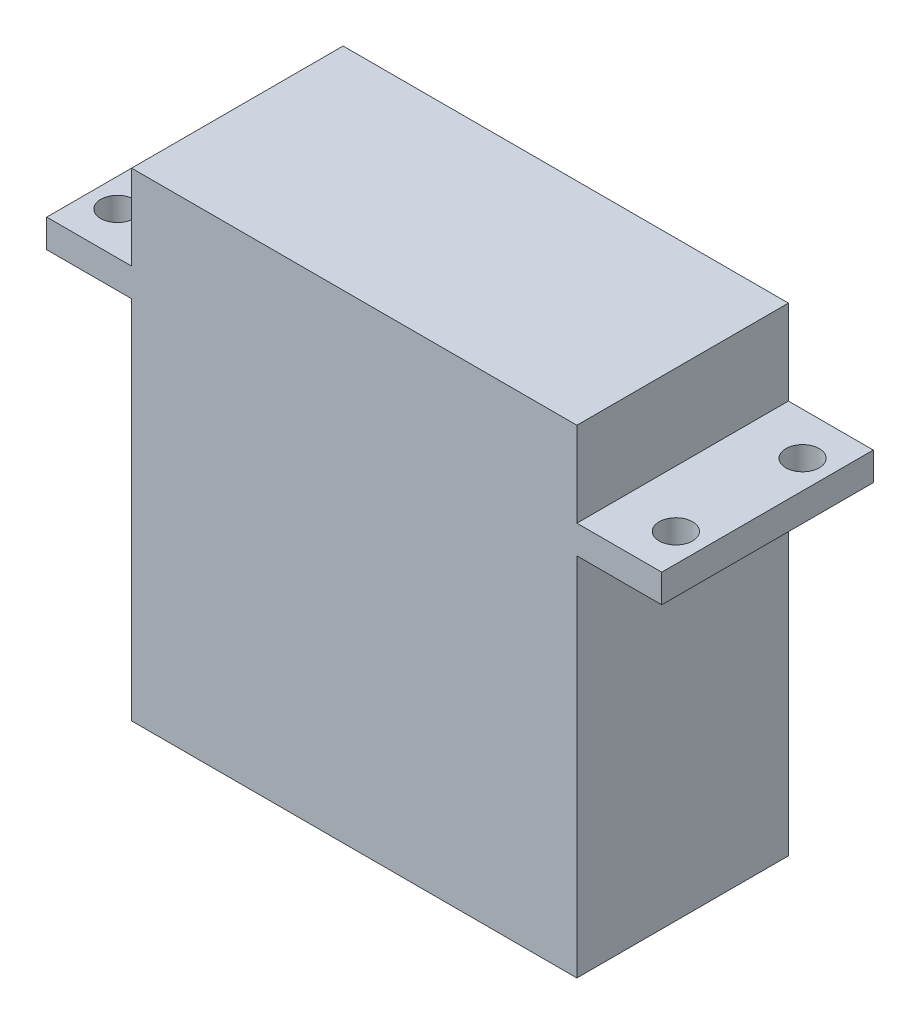
SolidWorks part; units mm, degrees
ref_plane "Front Plane" through (0, 0, 0) normal (0, 0, 1) x (1, 0, 0)
ref_plane "Top Plane" through (0, 0, 0) normal (0, 1, 0) x (1, 0, 0)
ref_plane "Right Plane" through (0, 0, 0) normal (1, 0, 0) x (0, 0, -1)
sketch "Sketch1" plane through (0, 0, 0) normal (0, 0, 1) x (1, 0, 0)
  line L1 (0, 0) -> (40, 0)
  line L2 (0, 0) -> (0, 43)
  line L3 (0, 43) -> (40, 43)
  line L4 (40, 0) -> (40, 43)
  dimension "D1" = 40
  dimension "D2" = 43
extrude "Boss-Extrude1" add sketch "Sketch1" along normal blind 19
sketch "Sketch2" plane through (40, 0, 0) normal (1, 0, 0) x (0, 0, -1)
  line L0 (-19, 0) -> (-19, 43) construction
  line L1 (-19, 35.38) -> (0, 35.38)
  line L2 (-19, 35.38) -> (-19, 32.84)
  line L3 (-19, 32.84) -> (0, 32.84)
  line L4 (0, 35.38) -> (0, 32.84)
  line L5 (0, 0) -> (0, 43) construction
  line L6 (-19, 43) -> (0, 43) construction
  dimension "D1" = 2.54
  dimension "D2" = 7.62
extrude "Boss-Extrude2" add sketch "Sketch2" along normal blind 7.62
sketch "Sketch3" plane through (0, 35.38, 0) normal (0, 1, 0) x (1, 0, 0)
  line L0 (47.62, 0) -> (40, 0) construction
  line L1 (47.62, 0) -> (47.62, -19) construction
  line L2 (47.62, -19) -> (40, -19) construction
  circle A0 centre (45.08, -3.81) radius 1.5
  circle A1 centre (45.08, -15.19) radius 1.5
  dimension "D1" = 3
  dimension "D2" = 3.81
  dimension "D3" = 2.54
  dimension "D4" = 2.54
  dimension "D5" = 3.81
extrude "Cut-Extrude1" cut sketch "Sketch3" against normal through all
sketch "Sketch4" plane through (0, 0, 0) normal (-1, 0, 0) x (0, 0, 1)
  line L0 (0, 43) -> (0, 0) construction
  line L1 (0, 35.38) -> (19, 35.38)
  line L2 (0, 35.38) -> (0, 32.84)
  line L3 (0, 32.84) -> (19, 32.84)
  line L4 (19, 35.38) -> (19, 32.84)
  line L5 (19, 43) -> (19, 0) construction
  line L6 (19, 43) -> (0, 43) construction
  dimension "D1" = 2.54
  dimension "D2" = 7.62
extrude "Boss-Extrude3" add sketch "Sketch4" along normal blind 7.62
sketch "Sketch5" plane through (0, 35.38, 0) normal (0, 1, 0) x (1, 0, 0)
  line L0 (-7.62, 0) -> (0, 0) construction
  line L1 (-7.62, -19) -> (-7.62, 0) construction
  line L2 (-7.62, -19) -> (0, -19) construction
  circle A0 centre (-5.08, -3.81) radius 1.5
  circle A1 centre (-5.08, -15.19) radius 1.5
  dimension "D1" = 3
  dimension "D4" = 3.81
  dimension "D2" = 3.81
  dimension "D3" = 2.54
  dimension "D5" = 2.54
extrude "Cut-Extrude2" cut sketch "Sketch5" against normal through all
sketch "Sketch6" plane through (0, 43, 0) normal (0, 1, 0) x (1, 0, 0)
  line L0 (0, -19) -> (0, 0) construction
  line L2 (40, 0) -> (0, 0) construction
  point P0 (29.718, -9.525)
  point P5 (0, 0)
  dimension "D1" = 29.718
  dimension "D2" = 9.525
